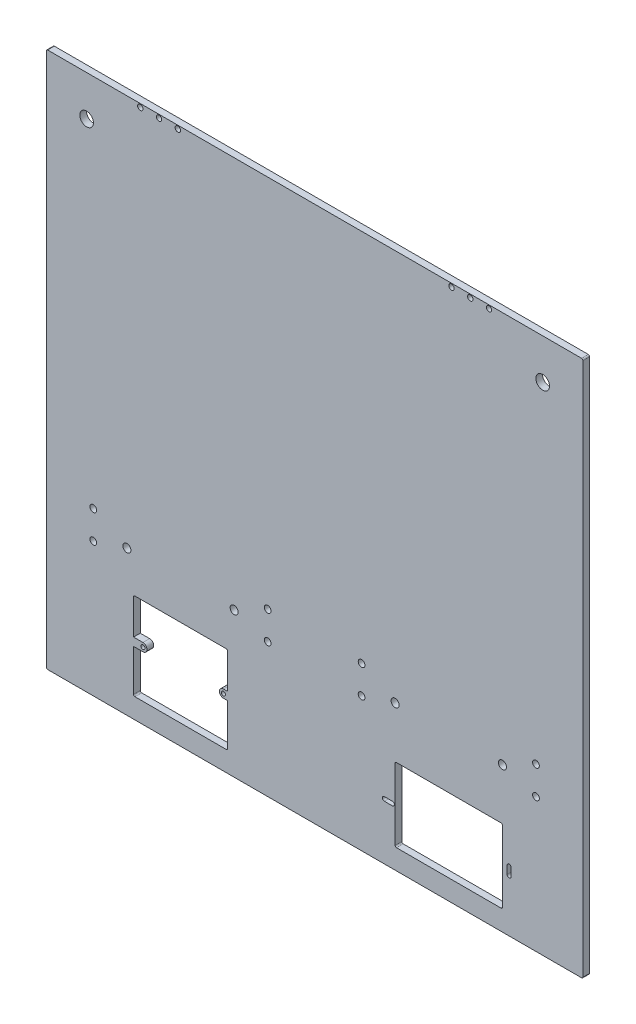
SolidWorks part; units mm, degrees
ref_plane "Front Plane" through (0, 0, 0) normal (0, 0, 1) x (1, 0, 0)
ref_plane "Top Plane" through (0, 0, 0) normal (0, 1, 0) x (1, 0, 0)
ref_plane "Right Plane" through (0, 0, 0) normal (1, 0, 0) x (0, 0, -1)
sketch "Sketch1" plane through (0, 0, 0) normal (0, 0, 1) x (1, 0, 0)
  line L0 (200, 400) -> (200, 0)
  line L1 (1, 0) -> (399, 0)
  line L2 (0, 1) -> (0, 399)
  line L3 (1, 400) -> (399, 400)
  line L4 (400, 1) -> (400, 399)
  line L5 (345, 45) -> (345, 39) construction
  line L6 (261, 70) -> (339, 70)
  line L7 (260, 69) -> (260, 16)
  line L8 (261, 15) -> (339, 15)
  line L9 (340, 69) -> (340, 16)
  line L10 (66, 80) -> (134, 80)
  line L11 (65, 79) -> (65, 16)
  line L12 (66, 15) -> (134, 15)
  line L13 (135, 79) -> (135, 16)
  line L14 (346.5, 45) -> (346.5, 39)
  line L15 (343.5, 45) -> (343.5, 39)
  line L16 (252, 42) -> (258, 42) construction
  line L21 (252, 43.5) -> (258, 43.5)
  line L22 (252, 40.5) -> (258, 40.5)
  circle A0 centre (35, 121) radius 2.5
  circle A1 centre (35, 100) radius 2.5
  circle A2 centre (60, 108) radius 3
  circle A3 centre (140, 108) radius 3
  circle A4 centre (165, 121) radius 2.5
  circle A5 centre (165, 100) radius 2.5
  circle A6 centre (235, 121) radius 2.5
  circle A7 centre (235, 100) radius 2.5
  circle A8 centre (260, 108) radius 3
  circle A9 centre (340, 108) radius 3
  circle A10 centre (365, 121) radius 2.5
  circle A11 centre (365, 100) radius 2.5
  arc A12 (339, 15) -> (340, 16) centre (339, 16) ccw
  arc A13 (261, 15) -> (260, 16) centre (261, 16) cw
  arc A14 (339, 70) -> (340, 69) centre (339, 69) cw
  arc A15 (260, 69) -> (261, 70) centre (261, 69) cw
  arc A16 (66, 15) -> (65, 16) centre (66, 16) cw
  arc A17 (135, 16) -> (134, 15) centre (134, 16) cw
  arc A18 (135, 79) -> (134, 80) centre (134, 79) ccw
  arc A19 (65, 79) -> (66, 80) centre (66, 79) cw
  arc A20 (0, 399) -> (1, 400) centre (1, 399) cw
  arc A21 (400, 399) -> (399, 400) centre (399, 399) ccw
  arc A22 (400, 1) -> (399, 0) centre (399, 1) cw
  arc A23 (1, 0) -> (0, 1) centre (1, 1) cw
  circle A24 centre (70, 397.5) radius 2
  circle A25 centre (84, 397.5) radius 2
  circle A26 centre (98, 397.5) radius 2
  circle A27 centre (302, 397.5) radius 2
  circle A28 centre (316, 397.5) radius 2
  circle A29 centre (330, 397.5) radius 2
  arc A30 (346.5, 45) -> (343.5, 45) centre (345, 45) ccw
  arc A31 (343.5, 39) -> (346.5, 39) centre (345, 39) ccw
  arc A37 (252, 43.5) -> (252, 40.5) centre (252, 42) ccw
  arc A38 (258, 40.5) -> (258, 43.5) centre (258, 42) ccw
  circle A39 centre (30, 370) radius 5.1
  circle A42 centre (370, 370) radius 5.1
  point P41 (340, 15)
  point P44 (260, 15)
  point P49 (260, 70)
  point P52 (65, 15)
  point P55 (135, 15)
  point P60 (65, 80)
  point P63 (0, 400)
  point P68 (400, 0)
  point P71 (0, 0)
  point P86 (345, 42)
  point P93 (255, 42)
  dimension "D3" = 15
  dimension "D10" = 21
  dimension "D25" = 21
  dimension "D31" = 21
  dimension "D32" = 21
  dimension "D35" = 1
  dimension "D36" = 14
  dimension "D37" = 14
  dimension "D42" = 14
  dimension "D43" = 28
  dimension "D44" = 2.5
  dimension "D47" = 30
  dimension "D48" = 30
  dimension "D50" = 30
  dimension "D51" = 30
  dimension "D1" = 400
  dimension "D2" = 400
  dimension "D4" = 15
  dimension "D5" = 70
  dimension "D6" = 65
  dimension "D7" = 55
  dimension "D8" = 80
  dimension "D9" = 35
  dimension "D11" = 35
  dimension "D12" = 60
  dimension "D13" = 60
  dimension "D14" = 35
  dimension "D15" = 35
  dimension "D16" = 60
  dimension "D17" = 35
  dimension "D18" = 35
  dimension "D19" = 35
  dimension "D20" = 35
  dimension "D21" = 60
  dimension "D22" = 20
  dimension "D23" = 28
  dimension "D24" = 20
  dimension "D26" = 28
  dimension "D27" = 30
  dimension "D28" = 38
  dimension "D29" = 30
  dimension "D30" = 38
  dimension "D33" = 65
  dimension "D34" = 60
  dimension "D38" = 70
  dimension "D39" = 2.5
  dimension "D40" = 2.5
  dimension "D41" = 2.5
  dimension "D45" = 70
  dimension "D46" = 27
  dimension "D49" = 5
extrude "Boss-Extrude1" add sketch "Sketch1" along normal blind 5 contours A23 L1 L0 L3 A20 L2 A26 A25 A24 L11 A19 L10 A18 L13 A17 L12 A16 A0 A1 A2 A3 A4 A5 | A22 L4 A21 L3 L0 L1 A29 A28 A27 A11 A10 A9 A8 A7 A6 L7 A15 L6 A14 L9 A12 L8 A13
sketch "Sketch2" plane through (0, 0, 0) normal (0, -1, 0) x (1, 0, 0)
  line L0 (1, 5) -> (399, 5) construction
  line L1 (1, 5) -> (1, 0) construction
  circle A0 centre (193, 2.5) radius 2
  circle A1 centre (207, 2.5) radius 2
  dimension "D1" = 2.5
  dimension "D3" = 14
  dimension "D2" = 2.5
  dimension "D4" = 192
extrude "Cut-Extrude1" cut sketch "Sketch2" against normal blind 8
sketch "Sketch3" plane through (0, 0, 0) normal (0, 0, 1) x (1, 0, 0)
  line L0 (65, 79) -> (65, 16) construction
  line L1 (66, 15) -> (134, 15) construction
  line L2 (135, 79) -> (135, 16) construction
  line L3 (72, 50) -> (65, 50) construction
  line L4 (72, 47) -> (65, 47)
  line L5 (72, 53) -> (65, 53)
  line L6 (132, 50) -> (135, 50) construction
  line L7 (132, 53) -> (135, 53)
  line L8 (132, 47) -> (135, 47)
  line L9 (65, 53) -> (65, 47)
  line L10 (135, 53) -> (135, 47)
  circle A0 centre (72, 50) radius 1.5
  circle A1 centre (132, 50) radius 1.5
  arc A2 (72, 47) -> (72, 53) centre (72, 50) ccw
  arc A3 (65, 53) -> (65, 47) centre (65, 50) ccw
  arc A4 (132, 53) -> (132, 47) centre (132, 50) ccw
  arc A5 (135, 47) -> (135, 53) centre (135, 50) ccw
  point P10 (68.5, 50)
  point P16 (133.5, 50)
  dimension "D1" = 7
  dimension "D2" = 35
  dimension "D3" = 35
  dimension "D4" = 3
extrude "Boss-Extrude2" add sketch "Sketch3" along normal blind 5 contours L7 A4 L8 L10 A1 | L4 A2 L5 L9 A0
